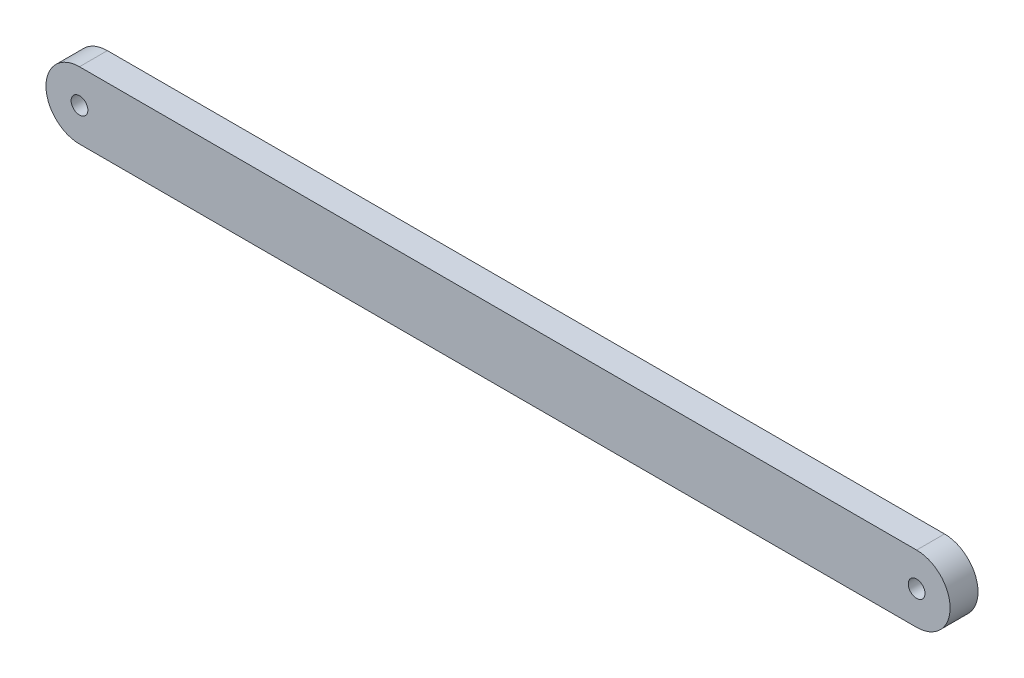
SolidWorks part; units mm, degrees
ref_plane "Plan de face" through (0, 0, 0) normal (0, 0, 1) x (1, 0, 0)
ref_plane "Plan de dessus" through (0, 0, 0) normal (0, 1, 0) x (1, 0, 0)
ref_plane "Plan de droite" through (0, 0, 0) normal (1, 0, 0) x (0, 0, -1)
sketch "Esquisse1" plane through (0, 0, 0) normal (0, 0, 1) x (1, 0, 0)
  line L0 (-75, 0) -> (75, 0) construction
  line L1 (-75, 6) -> (75, 6)
  line L2 (-75, -6) -> (75, -6)
  arc A0 (-75, 6) -> (-75, -6) centre (-75, 0) ccw
  arc A1 (75, -6) -> (75, 6) centre (75, 0) ccw
  circle A2 centre (-75, 0) radius 1.5
  circle A3 centre (75, 0) radius 1.5
  point P2 (0, 0)
  dimension "D1" = 6
  dimension "D3" = 3
  dimension "D4" = 3
  dimension "D2" = 150
extrude "Boss.-Extru.1" add sketch "Esquisse1" along normal blind 5
